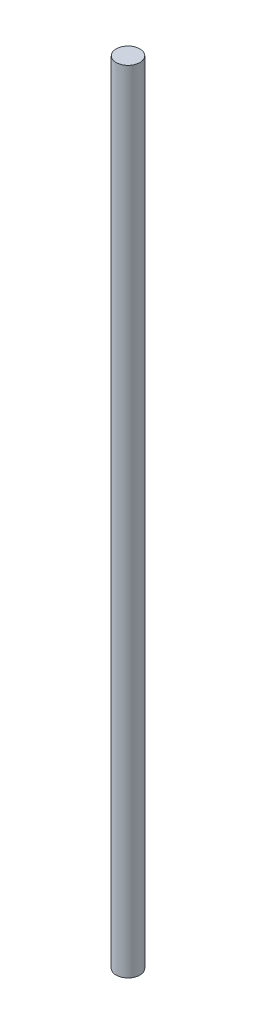
SolidWorks part; units mm, degrees
material "201 Annealed Stainless Steel (SS)"
ref_plane "Front Plane" through (0, 0, 0) normal (0, 0, 1) x (1, 0, 0)
ref_plane "Top Plane" through (0, 0, 0) normal (0, 1, 0) x (1, 0, 0)
ref_plane "Right Plane" through (0, 0, 0) normal (1, 0, 0) x (0, 0, -1)
sketch "Sketch1" plane through (0, 0, 0) normal (0, 1, 0) x (1, 0, 0)
  circle A0 centre (-5.3268, 0) radius 3
  dimension "D1" = 6
extrude "Boss-Extrude1" add sketch "Sketch1" along normal blind 200
